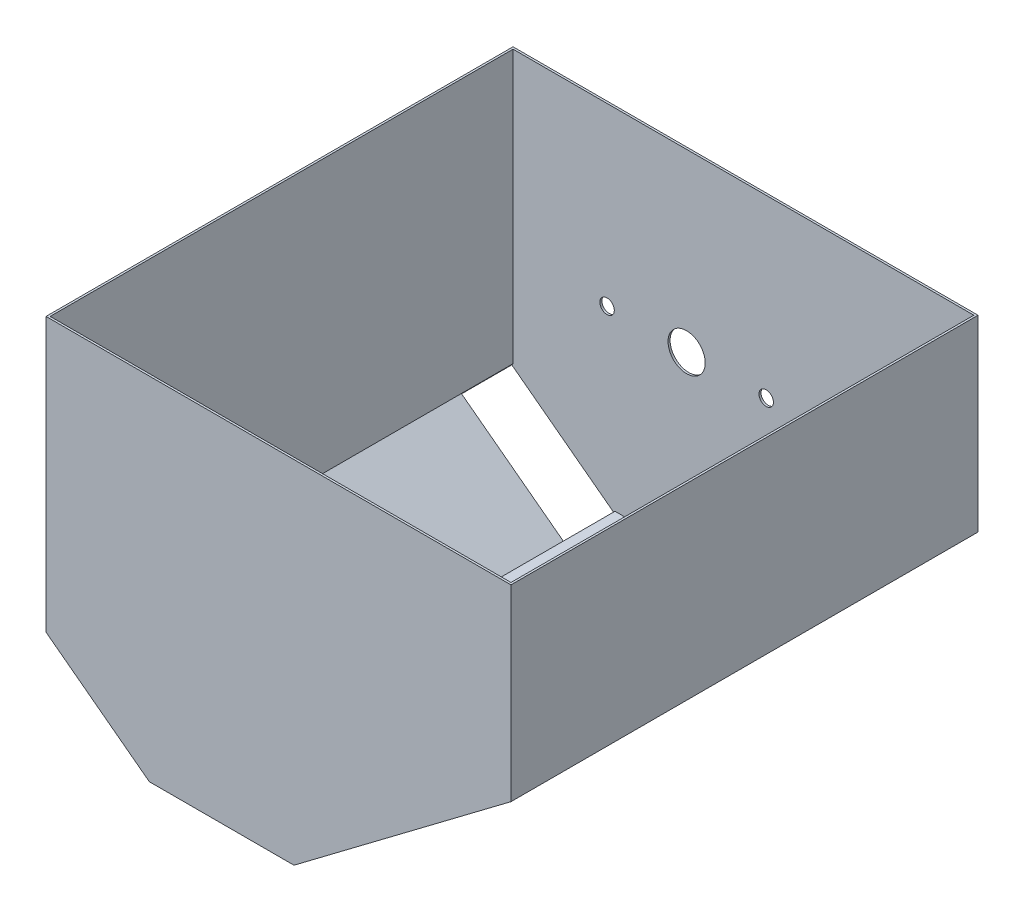
SolidWorks part; units mm, degrees
ref_plane "Alzado" through (0, 0, 0) normal (0, 0, 1) x (1, 0, 0)
ref_plane "Planta" through (0, 0, 0) normal (0, 1, 0) x (1, 0, 0)
ref_plane "Vista lateral" through (0, 0, 0) normal (1, 0, 0) x (0, 0, -1)
sketch "Croquis1" plane through (0, 0, 0) normal (0, 0, 1) x (1, 0, 0)
  line L0 (-70, -170) -> (70, -170)
  line L1 (70, -170) -> (280, -11.7536)
  line L2 (280, -11.7536) -> (280, 170)
  line L3 (280, 170) -> (-170, 170)
  line L4 (-170, 170) -> (-170, -94.6446)
  line L5 (-170, -94.6446) -> (-70, -170)
  line L6 (0, 0) -> (-170, 0) construction
  line L7 (0, 0) -> (0, -170) construction
  circle A0 centre (0, 0) radius 150 construction
  point P5 (0, -170)
  dimension "D1" = 300
  dimension "D2" = 37
  dimension "D3" = 37
  dimension "D4" = 170
  dimension "D5" = 140
  dimension "D6" = 340
  dimension "D7" = 450
extrude "Saliente-Extruir1" add sketch "Croquis1" along normal blind 2
sketch "Croquis2" plane through (0, 0, 2) normal (0, 0, 1) x (1, 0, 0)
  line L0 (-170, 170) -> (-168, 170)
  line L1 (280, 170) -> (-170, 170) construction
  line L2 (-170, 170) -> (-170, -94.6446) construction
  line L3 (-168, 170) -> (-168, -93.6474)
  line L4 (-168, -93.6474) -> (-69.3308, -168)
  line L5 (-69.3308, -168) -> (69.3308, -168)
  line L6 (69.3308, -168) -> (278, -10.7565)
  line L7 (278, -10.7565) -> (278, 170)
  line L8 (278, 170) -> (280, 170)
  line L9 (280, 170) -> (280, -11.7536)
  line L10 (280, -11.7536) -> (70, -170)
  line L11 (70, -170) -> (-70, -170)
  line L12 (-70, -170) -> (-170, -94.6446)
  line L13 (-170, -94.6446) -> (-170, 170)
  dimension "D1" = 2
  dimension "D2" = 2
  dimension "D3" = 2
  dimension "D4" = 2
  dimension "D5" = 2
extrude "Saliente-Extruir2" add sketch "Croquis2" along normal blind 450
sketch "Croquis3" plane through (0, 0, 452) normal (0, 0, 1) x (1, 0, 0)
  line L0 (-170, 170) -> (280, 170)
  line L1 (280, 170) -> (280, -11.7536)
  line L2 (280, -11.7536) -> (70, -170)
  line L3 (70, -170) -> (-70, -170)
  line L4 (-70, -170) -> (-170, -94.6446)
  line L5 (-170, -94.6446) -> (-170, 170)
extrude "Saliente-Extruir3" add sketch "Croquis3" against normal blind 2
sketch "Croquis4" plane through (0, 0, 2) normal (0, 0, 1) x (1, 0, 0)
  circle A0 centre (0, 0) radius 18
  dimension "D1" = 36
extrude "Cortar-Extruir1" cut sketch "Croquis4" against normal blind 2
sketch "Croquis5" plane through (-105.8563, -140.4761, 0) normal (0.6018, 0.7986, 0) x (0.7986, -0.6018, 0)
  line L0 (45.7349, -450) -> (45.7349, -2) construction
  line L1 (-77.8123, -2) -> (45.7349, -2)
  line L2 (-77.8123, -2) -> (-77.8123, -52)
  line L3 (-77.8123, -52) -> (45.7349, -52)
  line L4 (45.7349, -2) -> (45.7349, -52)
  dimension "D1" = 50
extrude "Cortar-Extruir2" cut sketch "Croquis5" against normal blind 2
sketch "Croquis6" plane through (0, 0, 0) normal (0, 0, -1) x (-1, 0, 0)
  line L0 (0, 0) -> (170, 0) construction
  line L1 (0, 32.8082) -> (0, -45.5513) construction
  line L2 (0, 0) -> (0, -170) construction
  circle A0 centre (77, 0) radius 7
  circle A1 centre (-77, 0) radius 7
  dimension "D1" = 14
  dimension "D2" = 77
extrude "Cortar-Extruir3" cut sketch "Croquis6" against normal blind 2
